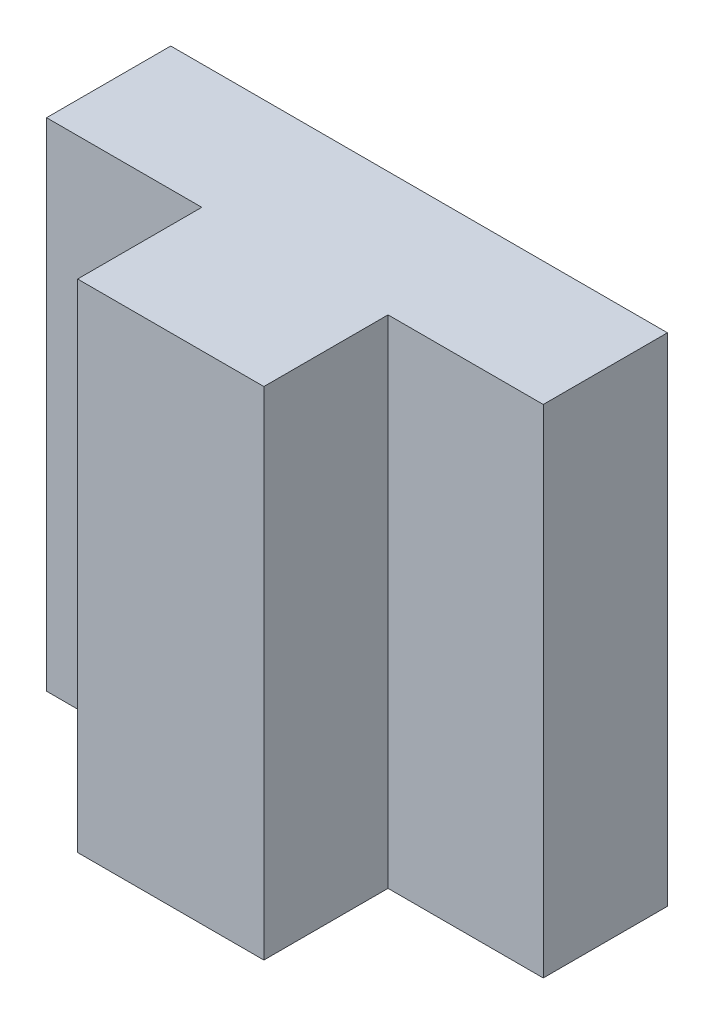
SolidWorks part; units mm, degrees
ref_plane "Front Plane" through (0, 0, 0) normal (0, 0, 1) x (1, 0, 0)
ref_plane "Top Plane" through (0, 0, 0) normal (0, 1, 0) x (1, 0, 0)
ref_plane "Right Plane" through (0, 0, 0) normal (1, 0, 0) x (0, 0, -1)
sketch "Sketch2" plane through (0, 0, 0) normal (0, 1, 0) x (1, 0, 0)
  line L1 (0, 0) -> (80, 0)
  line L2 (0, 0) -> (0, -20)
  line L3 (25, -40) -> (55, -40)
  line L4 (80, 0) -> (80, -20)
  line L7 (0, -20) -> (25, -20)
  line L8 (25, -40) -> (25, -20)
  line L11 (80, -20) -> (55, -20)
  line L12 (55, -40) -> (55, -20)
extrude "Boss-Extrude1" add sketch "Sketch2" along normal blind 80
